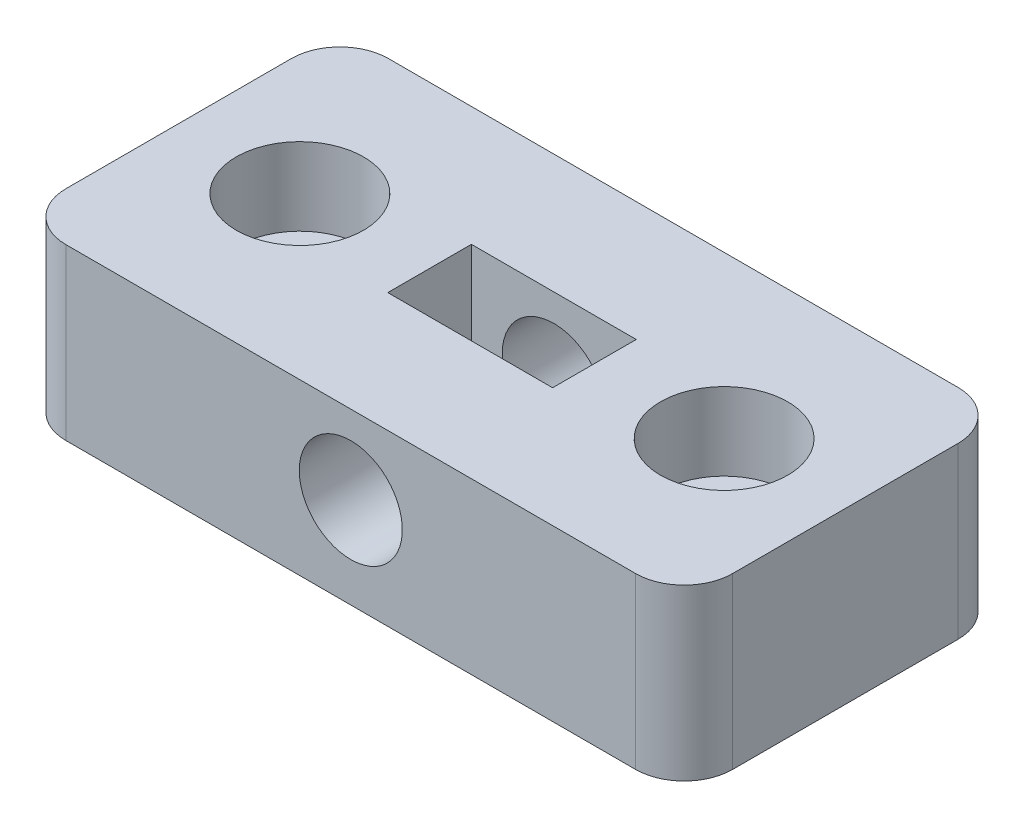
SolidWorks part; units mm, degrees
ref_plane "Front Plane" through (0, 0, 0) normal (0, 0, 1) x (1, 0, 0)
ref_plane "Top Plane" through (0, 0, 0) normal (0, 1, 0) x (1, 0, 0)
ref_plane "Right Plane" through (0, 0, 0) normal (1, 0, 0) x (0, 0, -1)
sketch "Sketch1" plane through (0, 0, 0) normal (0, 1, 0) x (1, 0, 0)
  line L0 (0, 29.2401) -> (0, -32.2189) construction
  line L1 (-27.5, 13.3) -> (27.5, 13.3)
  line L2 (-27.5, 13.3) -> (-27.5, -13.3)
  line L3 (-27.5, -13.3) -> (27.5, -13.3)
  line L4 (27.5, 13.3) -> (27.5, -13.3)
  line L5 (-27.5, 13.3) -> (27.5, -13.3) construction
  line L6 (-27.5, -13.3) -> (27.5, 13.3) construction
  circle A0 centre (-17.5, 0) radius 3.25
  circle A1 centre (17.5, 0) radius 3.25
  point P0 (0, 0)
  dimension "D3" = 6.5
  dimension "D1" = 55
  dimension "D2" = 26.6
  dimension "D4" = 10
  dimension "D5" = 13.3
extrude "Boss-Extrude1" add sketch "Sketch1" along normal blind 14
sketch "Sketch3" plane through (0, 14, 0) normal (0, 1, 0) x (1, 0, 0)
  line L1 (-6.8, 3.45) -> (6.8, 3.45)
  line L2 (-6.8, 3.45) -> (-6.8, -3.45)
  line L3 (-6.8, -3.45) -> (6.8, -3.45)
  line L4 (6.8, 3.45) -> (6.8, -3.45)
  line L5 (-6.8, 3.45) -> (6.8, -3.45) construction
  line L6 (-6.8, -3.45) -> (6.8, 3.45) construction
  point P0 (0, 0)
  dimension "D1" = 13.6
  dimension "D2" = 6.9
extrude "Cut-Extrude1" cut sketch "Sketch3" against normal blind 13
sketch "Sketch4" plane through (0, 0, -13.3) normal (0, 0, -1) x (-1, 0, 0)
  line L0 (-27.5, 14) -> (27.5, 14) construction
  circle A0 centre (0, 7.5) radius 4.25
  dimension "D1" = 8.5
  dimension "D2" = 6.5
extrude "Cut-Extrude2" cut sketch "Sketch4" against normal through all
sketch "Sketch5" plane through (0, 14, 0) normal (0, 1, 0) x (1, 0, 0)
  circle A0 centre (-17.5, 0) radius 5.25
  circle A1 centre (17.5, 0) radius 5.25
  circle A2 centre (-17.5, 0) radius 3.25 construction
  circle A3 centre (17.5, 0) radius 3.25 construction
  dimension "D1" = 10.5
  dimension "D2" = 10.5
extrude "Cut-Extrude3" cut sketch "Sketch5" against normal blind 6.4
fillet "Fillet1" radius 4 4 edges at (-27.5, 7, 13.3) (-27.5, 7, -13.3) (27.5, 7, 13.3) (27.5, 7, -13.3)
